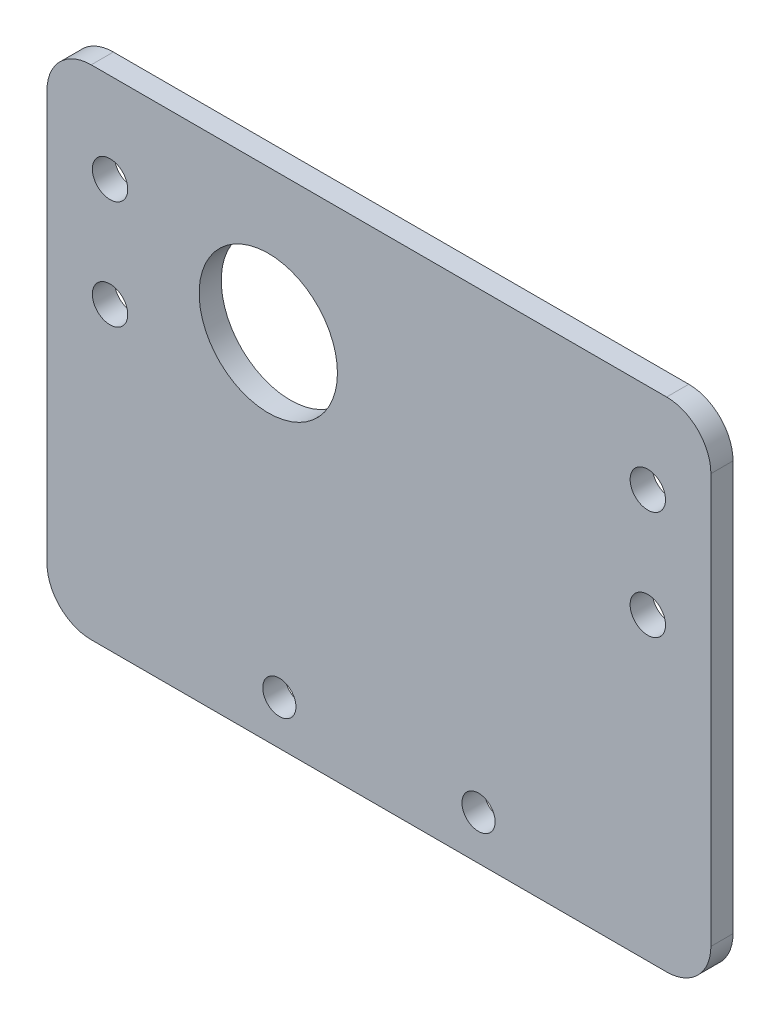
SolidWorks part; units mm, degrees
ref_plane "前视基准面" through (0, 0, 0) normal (0, 0, 1) x (1, 0, 0)
ref_plane "上视基准面" through (0, 0, 0) normal (0, 1, 0) x (1, 0, 0)
ref_plane "右视基准面" through (0, 0, 0) normal (1, 0, 0) x (0, 0, -1)
other "Configuration Table"
sketch "草图1" plane through (0, 0, 0) normal (0, 0, 1) x (1, 0, 0)
  line L1 (0, 0) -> (60, 0)
  line L2 (0, 0) -> (0, 45)
  line L3 (0, 45) -> (60, 45)
  line L4 (60, 0) -> (60, 45)
  dimension "D1" = 60
  dimension "D2" = 45
extrude "凸台-拉伸1" add sketch "草图1" along normal blind 2
fillet "圆角1" radius 4 4 edges at (60, 45, 1) (60, 0, 1) (0, 0, 1) (0, 45, 1)
sketch "草图2" plane through (0, 0, 0) normal (0, 0, -1) x (-1, 0, 0)
  line L0 (-60, 4) -> (0, 4) construction
  line L1 (-60, 4) -> (-60, 41) construction
  line L2 (0, 41) -> (0, 4) construction
  line L3 (-30, 0) -> (-30, 45) construction
  line L4 (-4, 0) -> (-56, 0) construction
  line L5 (-56, 45) -> (-4, 45) construction
  circle A0 centre (-39, 4) radius 1.5
  circle A1 centre (-21, 4) radius 1.5
  point P16 (-10.8396, 6.5832)
  dimension "D1" = 4
  dimension "D2" = 3
  dimension "D3" = 18
extrude "切除-拉伸1" cut sketch "草图2" against normal blind 2
sketch "草图3" plane through (0, 0, 2) normal (0, 0, 1) x (1, 0, 0)
  line L0 (0, 32) -> (60, 32) construction
  line L1 (0, 41) -> (0, 4) construction
  line L2 (60, 4) -> (60, 41) construction
  line L3 (30, 45) -> (30, 0) construction
  line L4 (56, 45) -> (4, 45) construction
  line L5 (4, 0) -> (56, 0) construction
  circle A1 centre (5.7, 36.9) radius 1.6
  circle A2 centre (5.7, 27.1) radius 1.6
  circle A3 centre (54.3, 36.9) radius 1.6
  circle A4 centre (54.3, 27.1) radius 1.6
  dimension "D1" = 3.2
  dimension "D2" = 13
  dimension "D3" = 48.6
  dimension "D4" = 9.8
extrude "切除-拉伸2" cut sketch "草图3" against normal blind 2
sketch "草图4" plane through (0, 0, 2) normal (0, 0, 1) x (1, 0, 0)
  line L0 (5.7, 36.9) -> (5.7, 27.1) construction
  line L1 (5.7, 32) -> (60, 32) construction
  line L2 (60, 4) -> (60, 41) construction
  circle A0 centre (20, 32) radius 6.25
  dimension "D2" = 12.5
  dimension "D1" = 14.3
extrude "切除-拉伸3" cut sketch "草图4" against normal blind 2
